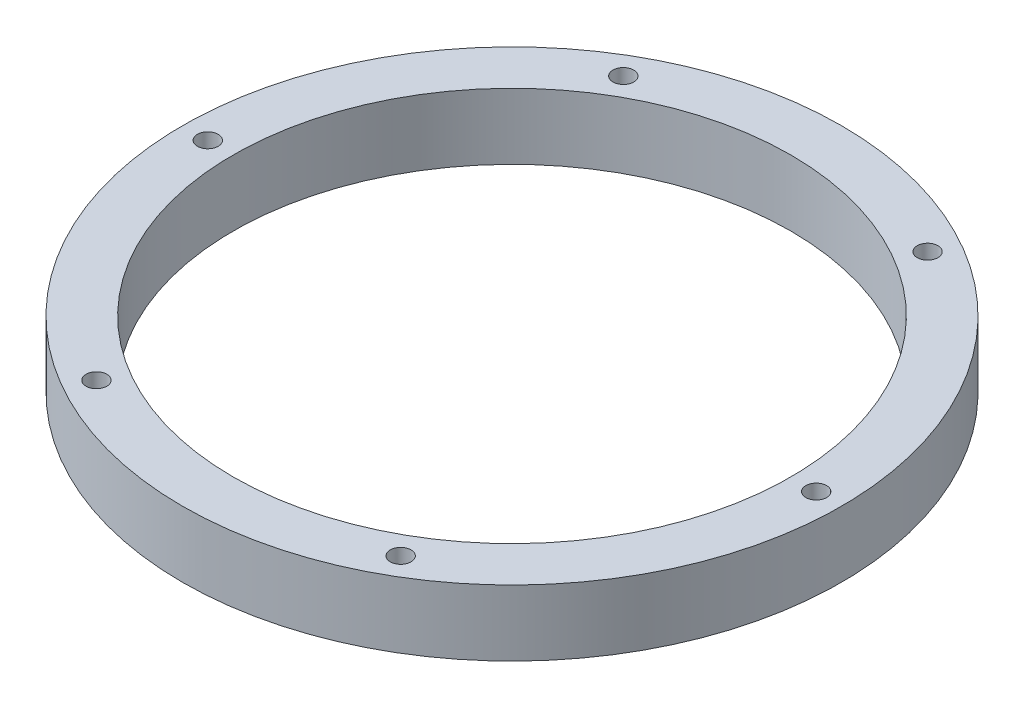
SolidWorks part; units mm, degrees
ref_plane "前视基准面" through (0, 0, 0) normal (0, 0, 1) x (1, 0, 0)
ref_plane "上视基准面" through (0, 0, 0) normal (0, 1, 0) x (1, 0, 0)
ref_plane "右视基准面" through (0, 0, 0) normal (1, 0, 0) x (0, 0, -1)
sketch "草图1" plane through (0, 0, 0) normal (0, 1, 0) x (1, 0, 0)
  circle A0 centre (0, 0) radius 55
  circle A1 centre (0, 0) radius 65
  circle A2 centre (60, 0) radius 2.05
  circle A3 centre (30, -51.9615) radius 2.05
  circle A4 centre (-30, -51.9615) radius 2.05
  circle A5 centre (-60, 0) radius 2.05
  circle A6 centre (-30, 51.9615) radius 2.05
  circle A7 centre (30, 51.9615) radius 2.05
  point P18 (0, 0)
  dimension "D1" = 110
  dimension "D2" = 130
  dimension "D4" = 6
  dimension "D5" = 4.1
  dimension "D3" = 60
extrude "凸台-拉伸1" add sketch "草图1" along normal blind 13
